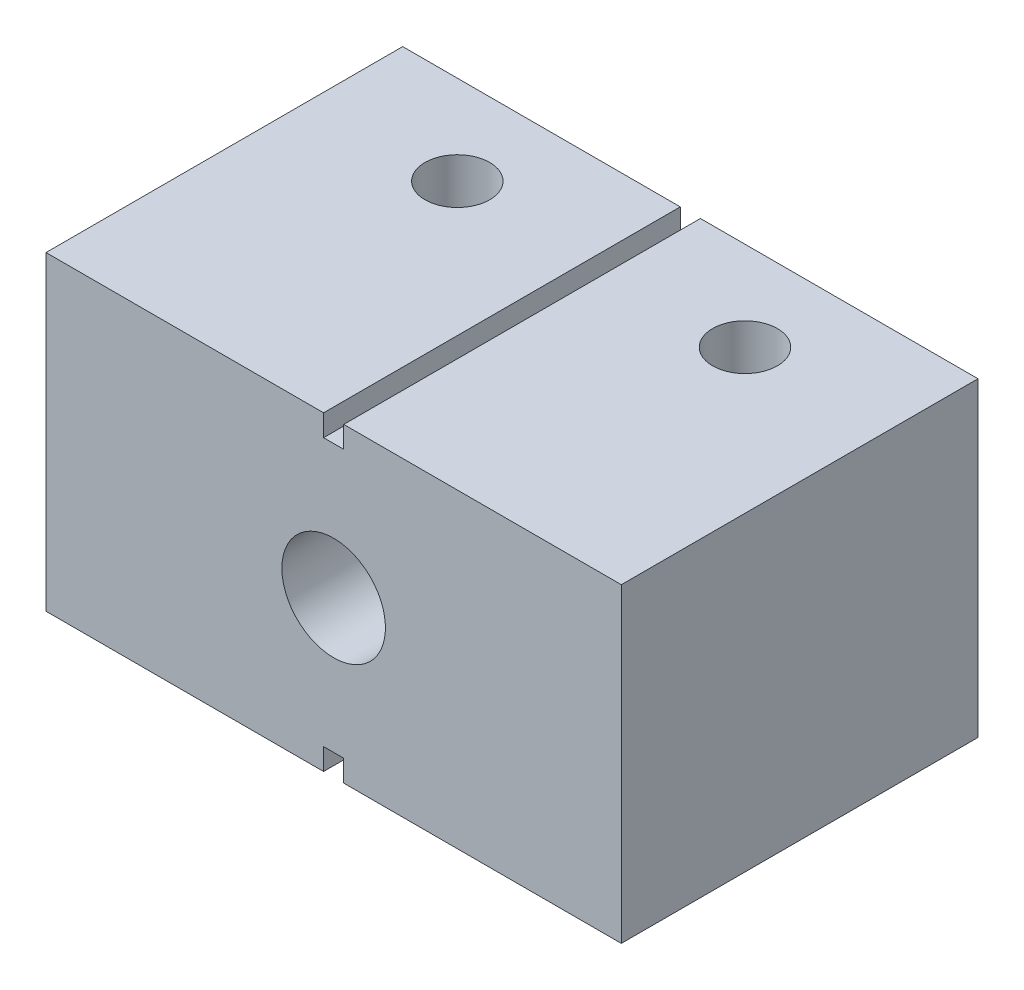
SolidWorks part; units mm, degrees
ref_plane "Front Plane" through (0, 0, 0) normal (0, 0, 1) x (1, 0, 0)
ref_plane "Top Plane" through (0, 0, 0) normal (0, 1, 0) x (1, 0, 0)
ref_plane "Right Plane" through (0, 0, 0) normal (1, 0, 0) x (0, 0, -1)
sketch "Sketch1" plane through (0, 0, 0) normal (0, 0, 1) x (1, 0, 0)
  line L1 (-20, 10.8) -> (20, 10.8)
  line L2 (-20, 10.8) -> (-20, -10.8)
  line L3 (-20, -10.8) -> (20, -10.8)
  line L4 (20, 10.8) -> (20, -10.8)
  line L5 (-20, 10.8) -> (20, -10.8) construction
  line L6 (-20, -10.8) -> (20, 10.8) construction
  circle A0 centre (0, 0) radius 3.6
  point P0 (0, 0)
  dimension "D3" = 7.2
  dimension "D1" = 21.6
  dimension "D2" = 40
extrude "Boss-Extrude1" add sketch "Sketch1" along normal blind 24.8
sketch "Sketch2" plane through (0, 10.8, 0) normal (0, 1, 0) x (1, 0, 0)
  line L0 (0, -24.8) -> (0, 0) construction
  line L1 (20, -24.8) -> (-20, -24.8) construction
  line L2 (0, 0) -> (-20, 0) construction
  line L3 (-20, 0) -> (0, -12.4) construction
  line L4 (0, -12.4) -> (20, 0) construction
  circle A0 centre (-10, -6.2) radius 2.25
  circle A1 centre (10, -6.2) radius 2.25
  dimension "D1" = 4.5
extrude "Cut-Extrude1" cut sketch "Sketch2" against normal up to next
sketch "Sketch3" plane through (0, 10.8, 0) normal (0, 1, 0) x (1, 0, 0)
  line L0 (20, -24.8) -> (-20, -24.8) construction
  line L1 (-0.7, -24.8) -> (0.7, -24.8)
  line L2 (-0.7, -24.8) -> (-0.7, 0)
  line L3 (-0.7, 0) -> (0.7, 0)
  line L4 (0.7, -24.8) -> (0.7, 0)
  line L5 (-0.7, -24.8) -> (0.7, 0) construction
  line L6 (-0.7, 0) -> (0.7, -24.8) construction
  line L7 (20, 0) -> (-20, 0) construction
  point P0 (0, -12.4)
  point P7 (0, -24.8)
  point P8 (0, -24.8)
  point P11 (0, 0)
  point P12 (0, 0)
  dimension "D1" = 1.4
extrude "Cut-Extrude2" cut sketch "Sketch3" against normal blind 1.5
sketch "Sketch4" plane through (0, -10.8, 0) normal (0, -1, 0) x (1, 0, 0)
  line L4 (0.7, 0) -> (0.7, 24.8)
  line L5 (-0.7, 0) -> (0.7, 0)
  line L6 (-0.7, 24.8) -> (-0.7, 0)
  line L7 (0.7, 24.8) -> (-0.7, 24.8)
  line L8 (0.7, 0) -> (0.7, 24.8)
  line L9 (-0.7, 0) -> (0.7, 0)
  line L10 (-0.7, 24.8) -> (-0.7, 0)
  line L11 (0.7, 24.8) -> (-0.7, 24.8)
  dimension "D1" = 0
extrude "Cut-Extrude3" cut sketch "Sketch4" against normal blind 1.5
sketch "Sketch5" plane through (0, 0, 0) normal (0, 0, -1) x (-1, 0, 0)
  line L0 (-20, -3.6) -> (0, -3.6) construction
  line L1 (-20, -10.8) -> (-20, 10.8) construction
  circle A0 centre (0, 0) radius 3.6 construction
  text T0 "18  " font "Century Gothic" height in points 28
  point P2 (6.0089, 7.3443)
  point P3 (17.067, 1.4188)
  point P4 (0, 0)
  point P5 (-20, -3.4635)
  point P9 (20, -4.465)
  point P10 (-3.1311, -1.7766)
extrude "Cut-Extrude4" cut sketch "Sketch5" against normal blind 1.2
